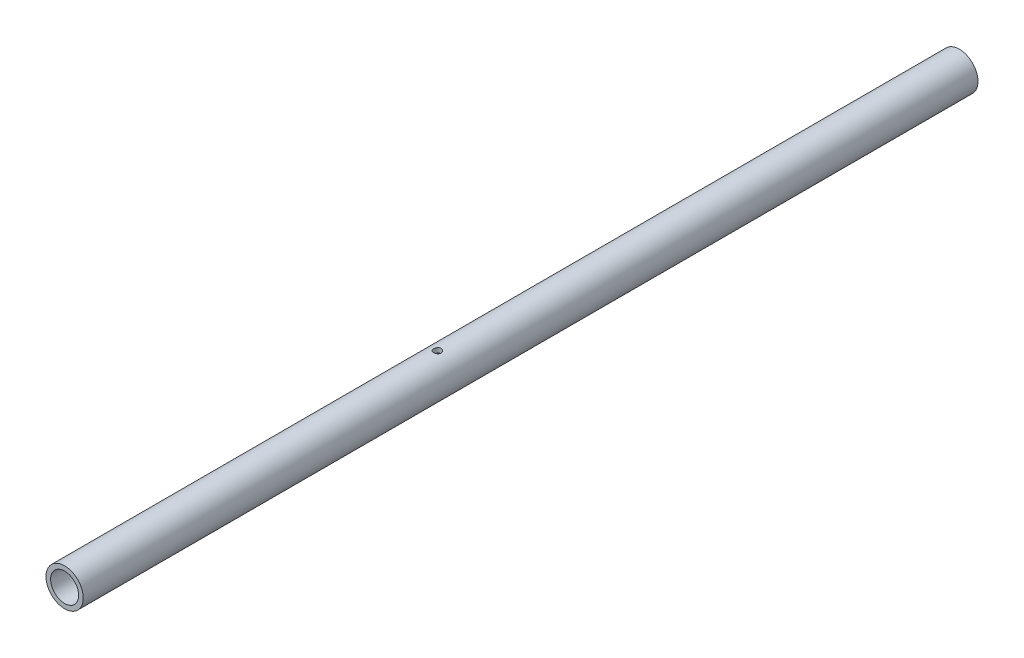
SolidWorks part; units mm, degrees
material "6061-T6 (SS)"
ref_plane "Front Plane" through (0, 0, 0) normal (0, 0, 1) x (1, 0, 0)
ref_plane "Top Plane" through (0, 0, 0) normal (0, 1, 0) x (1, 0, 0)
ref_plane "Right Plane" through (0, 0, 0) normal (1, 0, 0) x (0, 0, -1)
sketch "Sketch1" plane through (0, 0, 0) normal (0, 0, 1) x (1, 0, 0)
  circle A0 centre (-13.8623, 2.4097) radius 12.7
  circle A1 centre (-13.8623, 2.4097) radius 9.5567
  dimension "D1" = 25.4
  dimension "D2" = 19.1135
extrude "Boss-Extrude1" add sketch "Sketch1" along normal blind 609.6
sketch "Alignment Pin Bolt Hole Pattern " plane through (0, 0, 0) normal (0, 1, 0) x (1, 0, 0)
  line L0 (-1.1623, 0) -> (-26.5623, 0) construction
  point P0 (-13.8623, -355.6)
  dimension "D1" = 355.6
  dimension "D2" = 12.7
hole_wizard "Alignment Pin Bolt Hole (Clearance for 10-32)" positions "Sketch5" profile "Sketch4" hole size "#10" standard "ANSI Inch"
sketch "Sketch5" plane through (0, 0, 0) normal (0, 1, 0) x (1, 0, 0)
  point P0 (-13.8623, -355.6)
sketch "Sketch4" plane through (-13.8623, 0, 355.6) normal (1, 0, 0) x (0, 0, -1)
  line L0 (0, 0) -> (0, 15.1097)
  line L1 (0, 15.1097) -> (2.5527, 15.1097)
  line L2 (2.5527, 15.1097) -> (2.5527, 0)
  line L5 (2.5527, 0) -> (0, 0)
  line L11 (0, -6.35) -> (0, 107.95) construction
  dimension "Thru Hole Dia." = 5.1054
  dimension "Thru Hole Depth" = 15.1097
